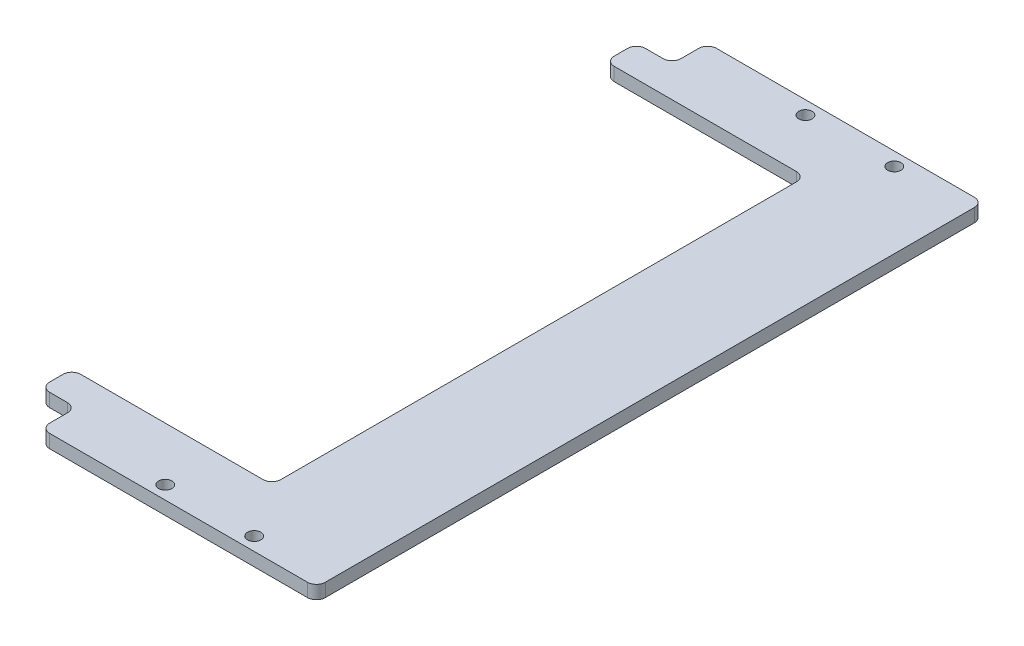
SolidWorks part; units mm, degrees
ref_plane "前视基准面" through (0, 0, 0) normal (0, 0, 1) x (1, 0, 0)
ref_plane "上视基准面" through (0, 0, 0) normal (0, 1, 0) x (1, 0, 0)
ref_plane "右视基准面" through (0, 0, 0) normal (1, 0, 0) x (0, 0, -1)
other "Configuration Table"
sketch "草图1" plane through (0, 0, 0) normal (0, 1, 0) x (1, 0, 0)
  line L0 (0, 0) -> (70, 0)
  line L1 (70, 0) -> (70, 150)
  line L2 (70, 150) -> (0, 150)
  line L3 (0, 150) -> (0, 135)
  line L4 (0, 135) -> (45, 135)
  line L5 (45, 135) -> (45, 15)
  line L6 (45, 15) -> (0, 15)
  line L7 (0, 15) -> (0, 0)
  line L8 (0, 15) -> (0, 135) construction
  dimension "D1" = 150
  dimension "D2" = 70
  dimension "D3" = 45
  dimension "D4" = 120
extrude "凸台-拉伸1" add sketch "草图1" along normal blind 3
sketch "草图2" plane through (0, 3, 0) normal (0, 1, 0) x (1, 0, 0)
  line L0 (70, 75) -> (45, 75) construction
  line L1 (0, 0) -> (8, 0)
  line L2 (0, 0) -> (0, 8)
  line L3 (0, 8) -> (8, 8)
  line L4 (8, 0) -> (8, 8)
  line L5 (70, 0) -> (70, 150) construction
  line L6 (45, 135) -> (45, 15) construction
  line L7 (0, 142) -> (8, 142)
  line L8 (8, 150) -> (8, 142)
  line L9 (0, 150) -> (8, 150)
  line L10 (0, 150) -> (0, 142)
  dimension "D1" = 8
  dimension "D2" = 8
extrude "切除-拉伸1" cut sketch "草图2" against normal blind 10
sketch "草图3" plane through (0, 3, 0) normal (0, 1, 0) x (1, 0, 0)
  line L0 (33, 3) -> (53, 3) construction
  line L1 (0, 15) -> (0, 8) construction
  line L2 (8, 0) -> (70, 0) construction
  line L3 (70, 75) -> (45, 75) construction
  line L4 (70, 0) -> (70, 150) construction
  line L5 (45, 135) -> (45, 15) construction
  line L6 (33, 147) -> (53, 147) construction
  circle A0 centre (33, 3) radius 1.5
  circle A1 centre (53, 3) radius 1.5
  circle A2 centre (53, 147) radius 1.5
  circle A3 centre (33, 147) radius 1.5
  dimension "D1" = 3
  dimension "D2" = 20
  dimension "D3" = 33
  dimension "D4" = 3
extrude "切除-拉伸2" cut sketch "草图3" against normal blind 10
fillet "圆角1" radius 2 12 edges at (70, 1.5, 0) (70, 1.5, -150) (8, 1.5, -150) (8, 1.5, -142) (0, 1.5, -142) (0, 1.5, -135) (45, 1.5, -135) (45, 1.5, -15) (0, 1.5, -15) (0, 1.5, -8) (8, 1.5, -8) (8, 1.5, 0)
